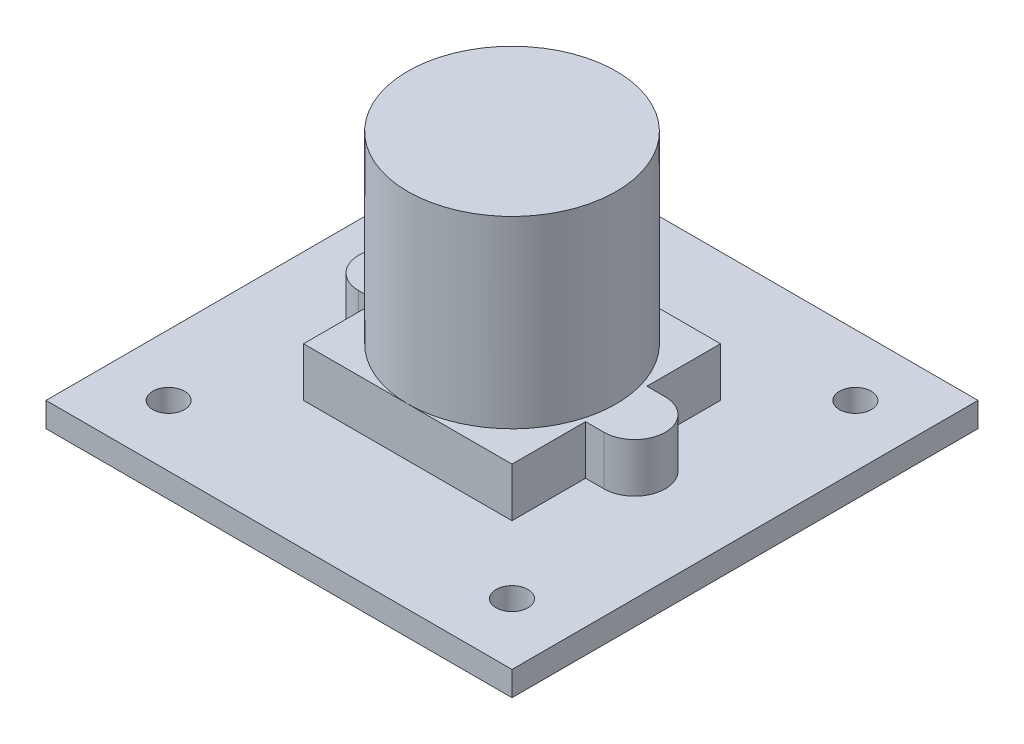
SolidWorks part; units mm, degrees
ref_plane "前视基准面" through (0, 0, 0) normal (0, 0, 1) x (1, 0, 0)
ref_plane "上视基准面" through (0, 0, 0) normal (0, 1, 0) x (1, 0, 0)
ref_plane "右视基准面" through (0, 0, 0) normal (1, 0, 0) x (0, 0, -1)
sketch "草图1" plane through (0, 0, 0) normal (0, 1, 0) x (1, 0, 0)
  line L1 (-19, 19) -> (19, 19)
  line L2 (-19, 19) -> (-19, -19)
  line L3 (-19, -19) -> (19, -19)
  line L4 (19, 19) -> (19, -19)
  line L5 (-19, 19) -> (19, -19) construction
  line L6 (-19, -19) -> (19, 19) construction
  line L7 (-14, 14) -> (14, 14) construction
  line L8 (-14, 14) -> (-14, -14) construction
  line L9 (-14, -14) -> (14, -14) construction
  line L10 (14, 14) -> (14, -14) construction
  line L11 (-14, 14) -> (14, -14) construction
  line L12 (-14, -14) -> (14, 14) construction
  circle A0 centre (-14, -14) radius 1.3
  circle A1 centre (-14, 14) radius 1.3
  circle A2 centre (14, 14) radius 1.3
  circle A3 centre (14, -14) radius 1.3
  point P0 (0, 0)
  point P6 (0, 0)
  dimension "D3" = 2.6
  dimension "D1" = 38
  dimension "D2" = 28
extrude "凸台-拉伸1" add sketch "草图1" along normal blind 2
sketch "草图2" plane through (0, 2, 0) normal (0, 1, 0) x (1, 0, 0)
  line L1 (-8.5, 8.5) -> (8.5, 8.5)
  line L2 (-8.5, 8.5) -> (-8.5, -8.5)
  line L3 (-8.5, -8.5) -> (8.5, -8.5)
  line L4 (8.5, 8.5) -> (8.5, -8.5)
  line L5 (-8.5, 8.5) -> (8.5, -8.5) construction
  line L6 (-8.5, -8.5) -> (8.5, 8.5) construction
  point P0 (0, 0)
  dimension "D1" = 17
extrude "凸台-拉伸2" add sketch "草图2" along normal blind 4
sketch "草图3" plane through (0, 6, 0) normal (0, 1, 0) x (1, 0, 0)
  circle A0 centre (0, 0) radius 8.5
  dimension "D1" = 17
extrude "凸台-拉伸3" add sketch "草图3" along normal blind 15
sketch "草图4" plane through (0, 2, 0) normal (0, 1, 0) x (1, 0, 0)
  line L0 (-10, 0) -> (10, 0) construction
  line L1 (-10, 2.5) -> (10, 2.5)
  line L2 (-10, -2.5) -> (10, -2.5)
  arc A0 (-10, 2.5) -> (-10, -2.5) centre (-10, 0) ccw
  arc A1 (10, -2.5) -> (10, 2.5) centre (10, 0) ccw
  point P2 (0, 0)
  dimension "D2" = 2.5
  dimension "D1" = 20
extrude "凸台-拉伸4" add sketch "草图4" along normal up to surface (4 mm away) up to face at (-6.2535, 6, -6.2535)
